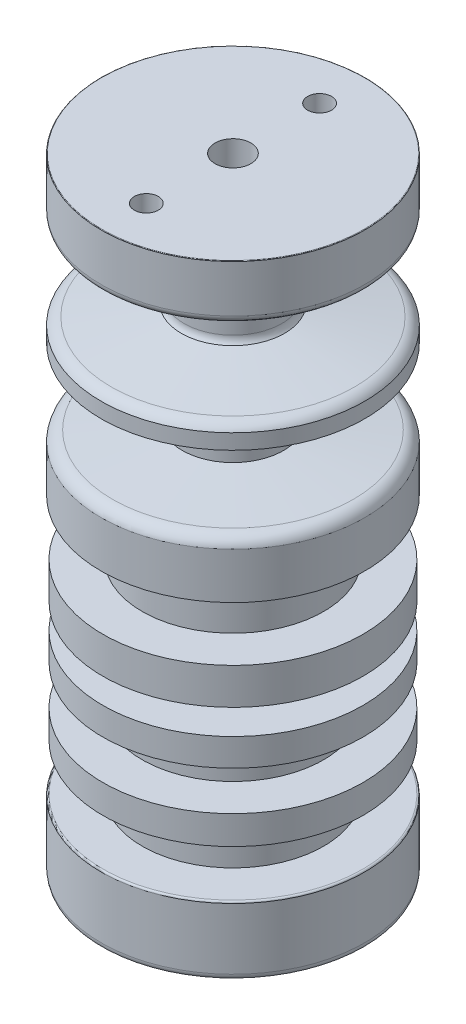
SolidWorks part; units mm, degrees
ref_plane "Alzado" through (0, 0, 0) normal (0, 0, 1) x (1, 0, 0)
ref_plane "Planta" through (0, 0, 0) normal (0, 1, 0) x (1, 0, 0)
ref_plane "Vista lateral" through (0, 0, 0) normal (1, 0, 0) x (0, 0, -1)
sketch "Croquis1" plane through (0, 0, 0) normal (0, 0, 1) x (1, 0, 0)
  line L0 (0, 0) -> (0, 43.0446) construction
  line L1 (0, 43.0446) -> (0, -121.9554) construction
  line L2 (0, 43.0446) -> (34.8584, 43.0446)
  line L3 (35, 42.903) -> (35, 30.366)
  line L4 (32.9644, 28.3304) -> (12.9858, 28.3304)
  line L5 (12.9858, 28.3304) -> (12.9858, 10.4062)
  line L6 (13.718, 8.5125) -> (32.3097, 5.486)
  line L7 (35, 3.5416) -> (35, -0.4901)
  line L8 (13.4687, -0.4901) -> (35, -0.4901)
  line L9 (13.4687, -0.4901) -> (13.4687, -18.5388)
  line L10 (13.4687, -18.5388) -> (31.9792, -20.5132)
  line L11 (35, -23.2242) -> (35, -35.5011)
  line L12 (24.0861, -91.9234) -> (34.5383, -91.9234)
  line L13 (24.0861, -91.9234) -> (24.0861, -104.2217)
  line L14 (24.0861, -104.2217) -> (34.5383, -104.2217)
  line L15 (35, -104.6833) -> (35, -120.9509)
  line L16 (34.7378, -121.991) -> (0, -121.9554)
  line L17 (0, 43.0446) -> (0, -121.9554)
  line L18 (34.5383, -91.9234) -> (34.5383, -84.3501)
  line L19 (35, -35.5011) -> (24.0861, -35.5011)
  line L20 (24.0861, -35.5011) -> (24.0861, -50.2633)
  line L21 (34.5383, -84.3501) -> (24.0861, -84.3501)
  line L22 (24.0861, -73.9073) -> (34.5383, -73.9073)
  line L23 (34.5383, -73.9073) -> (34.5383, -66.6171)
  line L24 (34.5383, -66.6171) -> (24.0861, -66.6171)
  line L25 (24.0861, -59.9179) -> (34.5383, -59.9179)
  line L26 (34.5383, -59.9179) -> (34.5383, -50.2633)
  line L27 (34.5383, -50.2633) -> (24.0861, -50.2633)
  line L28 (24.0861, -73.9073) -> (24.0861, -84.3501)
  line L29 (24.0861, -59.9179) -> (24.0861, -66.6171)
  arc A0 (34.8584, 43.0446) -> (35, 42.903) centre (34.8584, 42.903) cw
  arc A1 (35, 30.366) -> (32.9644, 28.3304) centre (32.9644, 30.366) cw
  arc A2 (12.9858, 10.4062) -> (13.718, 8.5125) centre (15.8008, 10.4062) ccw
  arc A3 (32.3097, 5.486) -> (35, 3.5416) centre (31.7144, 1.829) cw
  arc A6 (31.9792, -20.5132) -> (35, -23.2242) centre (31.6114, -23.9615) cw
  arc A8 (34.5383, -104.2217) -> (35, -104.6833) centre (34.5383, -104.6833) cw
  arc A9 (35, -120.9509) -> (34.7378, -121.991) centre (32.8058, -120.9509) cw
  dimension "D1" = 165
  dimension "D2" = 34.8584
  dimension "D3" = 35
  dimension "D4" = 35
  dimension "D5" = 35
revolve "Revolución3" add sketch "Croquis1" angle 360 about L17
sketch "Croquis2" plane through (0, 43.0446, 0) normal (0, 1, 0) x (1, 0, 0)
  line L1 (-0.2111, -19.8252) -> (0, 0) construction
  line L2 (0, 0) -> (11.2888, 0) construction
  line L4 (34.8584, 0) -> (-34.8584, 0) construction
  line L5 (-34.8584, 0) -> (0, 0) construction
  line L6 (0, 0) -> (0, 34.8584) construction
  line L7 (0, 34.8584) -> (0, -34.8584) construction
  circle A0 centre (0, 23) radius 3.175
  circle A1 centre (0, 0) radius 34.8584 construction
  circle A2 centre (0, -23) radius 3.175
  point P4 (0, 0)
  point P7 (0, 0)
  dimension "D3" = 6.35
  dimension "D4" = 6.35
  dimension "D1" = 23
  dimension "D2" = 23
extrude "Cortar-Extruir2" cut sketch "Croquis2" against normal blind 12
sketch "Croquis6" plane through (0, 43.0446, 0) normal (0, 1, 0) x (1, 0, 0)
  circle A0 centre (0, 0) radius 4.7625
  dimension "D1" = 9.525
extrude "Cortar-Extruir4" cut sketch "Croquis6" against normal blind 12
ref_plane "Plano1" through (0, 0, 0) normal (1, 0, 0) x (0, 0, -1)
ref_plane "Plano2" through (0, 0, 0) normal (0, 0, 1) x (1, 0, 0)
ref_plane "Plano3" through (0, -126.9554, 0) normal (0, 1, 0) x (1, 0, 0)
sketch "Croquis11" plane through (0, -126.9554, 0) normal (0, 1, 0) x (1, 0, 0)
  circle A0 centre (0, 0) radius 7.9375
  dimension "D1" = 15.875
extrude "Cortar-Extruir7" cut sketch "Croquis11" along normal blind 15.875
